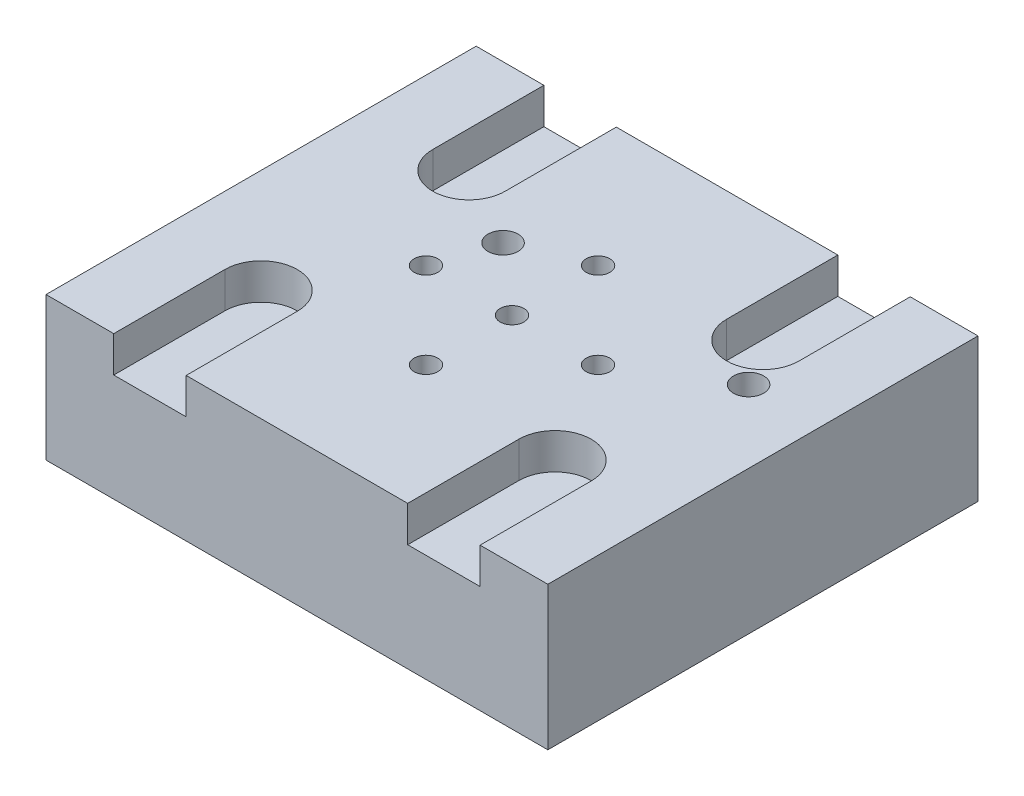
SolidWorks part; units mm, degrees
ref_plane "Front Plane" through (0, 0, 0) normal (0, 0, 1) x (1, 0, 0)
ref_plane "Top Plane" through (0, 0, 0) normal (0, 1, 0) x (1, 0, 0)
ref_plane "Right Plane" through (0, 0, 0) normal (1, 0, 0) x (0, 0, -1)
sketch "Sketch3" plane through (0, 0, 0) normal (0, 1, 0) x (1, 0, 0)
  line L1 (0, 0) -> (70, 0)
  line L2 (0, 0) -> (0, -60)
  line L3 (0, -60) -> (70, -60)
  line L4 (70, 0) -> (70, -60)
  dimension "D1" = 70
  dimension "D2" = 60
extrude "Boss-Extrude3" add sketch "Sketch3" along normal blind 20
sketch "Sketch4" plane through (0, 20, 0) normal (0, 1, 0) x (1, 0, 0)
  line L0 (35, 0) -> (35, -60) construction
  line L1 (70, 0) -> (0, 0) construction
  line L2 (0, -60) -> (70, -60) construction
  line L3 (0, -30) -> (70, -30) construction
  line L4 (0, 0) -> (0, -60) construction
  line L5 (70, -60) -> (70, 0) construction
  line L6 (21.35, -30) -> (21.35, 0) construction
  line L7 (0, 0) -> (70, 0) construction
  line L8 (24.65, -30) -> (24.65, 0) construction
  line L9 (45.35, -30) -> (45.35, 0) construction
  line L10 (48.65, -30) -> (48.65, 0) construction
  circle A0 centre (35, -30) radius 1.65
  circle A1 centre (35, -18) radius 1.65
  circle A2 centre (47, -30) radius 1.65
  circle A3 centre (35, -42) radius 1.65
  circle A4 centre (23, -30) radius 1.65
  dimension "D1" = 3.3
  dimension "D2" = 12
  dimension "D3" = 12
  dimension "D4" = 12
  dimension "D5" = 12
extrude "Cut-Extrude1" cut sketch "Sketch4" against normal through all
sketch "Sketch6" plane through (0, 0, 0) normal (0, -1, 0) x (1, 0, 0)
  line L0 (70, 30) -> (0, 30) construction
  line L1 (51.75, 21.875) -> (33.75, 21.875) construction
  line L2 (68, 21.875) -> (70, 21.875) construction
  line L3 (70, 60) -> (70, 0) construction
  line L4 (0, 0) -> (0, 60) construction
  line L5 (25.625, 21.875) -> (25.625, 0) construction
  line L6 (70, 0) -> (0, 0) construction
  line L7 (59.875, 21.875) -> (59.875, 0) construction
  line L8 (33.75, 21.875) -> (33.75, 0) construction
  line L9 (51.75, 21.875) -> (51.75, 0) construction
  line L10 (17.5, 21.875) -> (17.5, 0) construction
  line L11 (68, 21.875) -> (68, 0) construction
  line L12 (57.775, 21.875) -> (57.775, 0) construction
  line L13 (61.975, 21.875) -> (61.975, 0) construction
  line L14 (27.725, 21.875) -> (27.725, 0) construction
  line L15 (23.525, 21.875) -> (23.525, 0) construction
  line L17 (34.9322, 16.3514) -> (34.9322, 0) construction
  circle A2 centre (59.875, 21.875) radius 8.125 construction
  circle A3 centre (25.625, 21.875) radius 8.125 construction
  circle A4 centre (59.875, 21.875) radius 2.1
  circle A5 centre (25.625, 21.875) radius 2.1
  circle A6 centre (35, 18) radius 1.65 construction
  dimension "D1" = 16.25
  dimension "D2" = 18
  dimension "D3" = 4.2
  dimension "D4" = 2
extrude "Cut-Extrude2" cut sketch "Sketch6" against normal through all contours A4 | A5
sketch "Sketch9" plane through (0, 0, 0) normal (0, 0, -1) x (-1, 0, 0)
  line L0 (-25.625, 0) -> (-25.625, 20) construction
  line L1 (-70, 20) -> (0, 20) construction
  line L2 (-59.875, 0) -> (-59.875, 20) construction
  line L3 (-68, 0) -> (-51.75, 0) construction
  line L4 (-17.5, 0) -> (-17.5, 20) construction
  line L5 (-33.75, 0) -> (-33.75, 20) construction
  line L6 (-51.75, 0) -> (-51.75, 20) construction
  line L7 (-68, 0) -> (-68, 20) construction
  line L8 (-57.775, 0) -> (-57.775, 20) construction
  line L9 (-61.975, 0) -> (-61.975, 20) construction
  line L10 (-27.725, 0) -> (-27.725, 20) construction
  line L11 (-23.525, 0) -> (-23.525, 20) construction
  line L12 (-57.775, 7.5) -> (-55.775, 7.5) construction
  line L13 (-52.525, 10.75) -> (-52.525, 20) construction
  line L14 (-12.85, 7.5) -> (0, 7.5) construction
  line L15 (-19.35, 7.5) -> (-21.35, 7.5) construction
  line L16 (-16.1, 20) -> (-16.1, 10.75) construction
  line L17 (0, 20) -> (0, 0) construction
  line L18 (-34.9322, 0) -> (-34.9322, 20) construction
  line L19 (-34.9322, 0) -> (-34.9322, 20) construction
  line L20 (-49.275, 7.5) -> (-34.9322, 7.5) construction
  line L21 (-21.35, 20) -> (-21.35, 0) construction
  line L22 (0, 0) -> (-70, 0) construction
  line L23 (-24.65, 20) -> (-24.65, 0) construction
  line L24 (-45.35, 20) -> (-45.35, 0) construction
  line L25 (-48.65, 20) -> (-48.65, 0) construction
  line L26 (0, 7.5) -> (0, 20) construction
  circle A0 centre (-52.525, 7.5) radius 3.25
  circle A1 centre (-16.1, 7.5) radius 3.25
  dimension "D1" = 6.5
  dimension "D2" = 2
  dimension "D3" = 2
  dimension "D4" = 12.5
extrude "Cut-Extrude3" cut sketch "Sketch9" against normal blind 40.25
sketch "Sketch11" plane through (0, 0, 0) normal (0, -1, 0) x (1, 0, 0)
  line L0 (70, 30) -> (0, 30) construction
  circle A0 centre (23, 30) radius 3
  circle A1 centre (35, 42) radius 3
  circle A2 centre (35, 30) radius 3
  circle A3 centre (35, 18) radius 3
  circle A4 centre (47, 30) radius 3
  circle M3 centre (35, 18) radius 1.65
  circle M4 centre (47, 30) radius 1.65
  circle M5 centre (35, 42) radius 1.65
  circle M6 centre (23, 30) radius 1.65
  circle M7 centre (35, 30) radius 1.65
  dimension "D1" = 6
extrude "Cut-Extrude4" cut sketch "Sketch11" against normal blind 3 contours A3 M3 | A2 M7 | A4 M4 | A0 M6 | A1 M5 | M5 | M6 | M7 | M4 | M3
chamfer "Chamfer1" distance 0.8 angle 45 2 edges at (49.275, 7.5, 0) (12.85, 7.5, 0)
sketch "Sketch12" plane through (0, 20, 0) normal (0, 1, 0) x (1, 0, 0)
  line L0 (35, -60.1049) -> (14.5, -60.1049) construction
  line L1 (35, 0.1049) -> (35, -60.1049) construction
  line L2 (14.5, -60.1049) -> (14.5, -44.5) construction
  line L3 (9.45, -60.1049) -> (9.45, -44.5)
  line L4 (19.55, -60.1049) -> (19.55, -44.5)
  line L5 (70, -30) -> (0, -30) construction
  line L6 (35, 0) -> (35, -60) construction
  line L7 (35, 0.1049) -> (14.5, 0.1049) construction
  line L8 (55.5, -60.1049) -> (55.5, -44.5) construction
  line L9 (60.55, -60.1049) -> (60.55, -44.5)
  line L10 (50.45, -60.1049) -> (50.45, -44.5)
  line L11 (55.5, 0.1049) -> (55.5, -15.5) construction
  line L12 (60.55, 0.1049) -> (60.55, -15.5)
  line L13 (50.45, 0.1049) -> (50.45, -15.5)
  line L14 (14.5, 0.1049) -> (14.5, -15.5) construction
  line L15 (9.45, 0.1049) -> (9.45, -15.5)
  line L16 (19.55, 0.1049) -> (19.55, -15.5)
  arc A0 (9.45, -60.1049) -> (19.55, -60.1049) centre (14.5, -60.1049) ccw
  arc A1 (19.55, -44.5) -> (9.45, -44.5) centre (14.5, -44.5) ccw
  arc A3 (60.55, -60.1049) -> (50.45, -60.1049) centre (55.5, -60.1049) cw
  arc A4 (50.45, -44.5) -> (60.55, -44.5) centre (55.5, -44.5) cw
  arc A6 (60.55, 0.1049) -> (50.45, 0.1049) centre (55.5, 0.1049) ccw
  arc A7 (50.45, -15.5) -> (60.55, -15.5) centre (55.5, -15.5) ccw
  arc A8 (9.45, 0.1049) -> (19.55, 0.1049) centre (14.5, 0.1049) cw
  arc A9 (19.55, -15.5) -> (9.45, -15.5) centre (14.5, -15.5) cw
  point P0 (14.5, -52.3025)
  point P19 (35, -30)
  point P23 (55.5, -52.3025)
  point P29 (55.5, -7.6975)
  point P36 (14.5, -7.6975)
  dimension "D4" = 5.05
  dimension "D1" = 20.5
extrude "Cut-Extrude5" cut sketch "Sketch12" against normal blind 5
